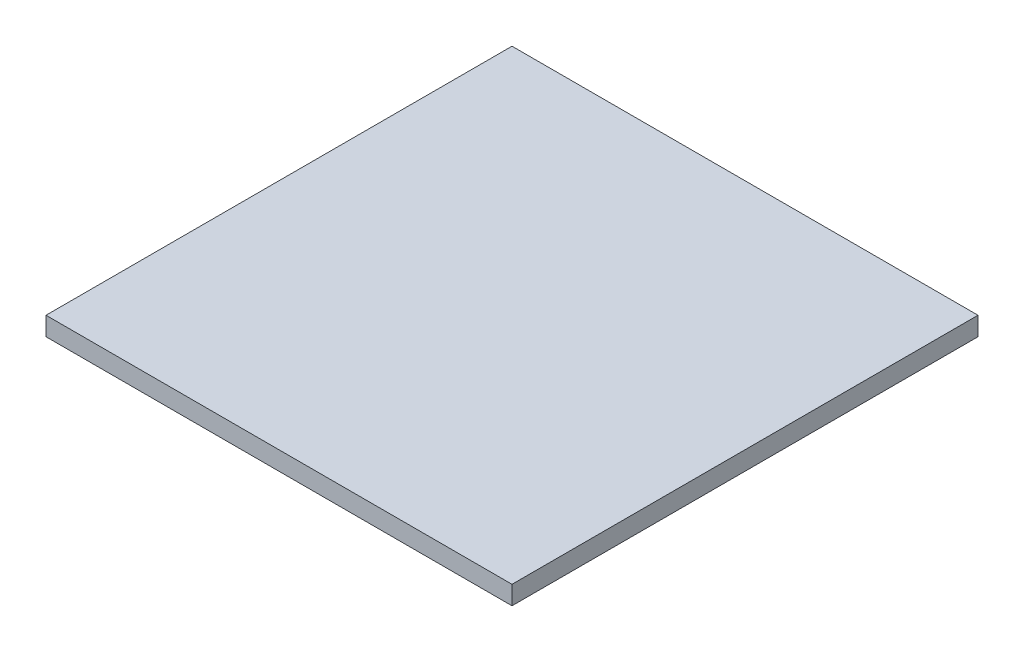
SolidWorks part; units mm, degrees
ref_plane "Front Plane" through (0, 0, 0) normal (0, 0, 1) x (1, 0, 0)
ref_plane "Top Plane" through (0, 0, 0) normal (0, 1, 0) x (1, 0, 0)
ref_plane "Right Plane" through (0, 0, 0) normal (1, 0, 0) x (0, 0, -1)
sketch "Sketch1" plane through (0, 0, 0) normal (0, 1, 0) x (1, 0, 0)
  line L1 (-250, -250) -> (250, -250)
  line L2 (-250, -250) -> (-250, 250)
  line L3 (-250, 250) -> (250, 250)
  line L4 (250, -250) -> (250, 250)
  line L5 (-250, -250) -> (250, 250) construction
  line L6 (-250, 250) -> (250, -250) construction
  point P0 (0, 0)
  dimension "D1" = 500
extrude "Boss-Extrude1" add sketch "Sketch1" along normal blind 20
